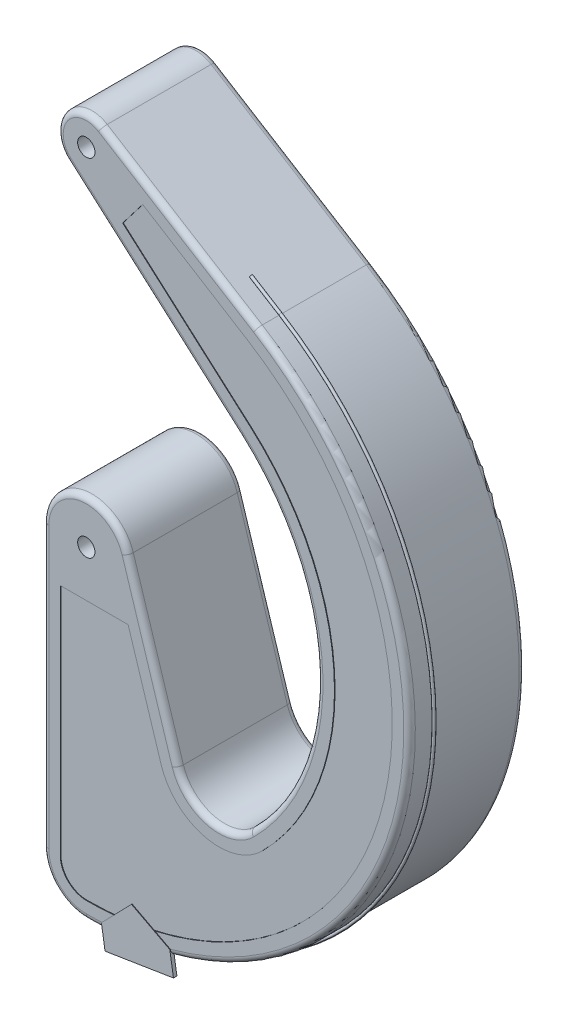
SolidWorks part; units mm, degrees
material "ABS"
ref_plane "Plan de face" through (0, 0, 0) normal (0, 0, 1) x (1, 0, 0)
ref_plane "Plan de dessus" through (0, 0, 0) normal (0, 1, 0) x (1, 0, 0)
ref_plane "Plan de droite" through (0, 0, 0) normal (1, 0, 0) x (0, 0, -1)
sketch "Esquisse1" plane through (0, 0, 0) normal (0, 0, 1) x (1, 0, 0)
  line L0 (0, 0) -> (0, -47.5) construction
  line L1 (0, 0) -> (22.981, -22.981) construction
  line L2 (-7.5, 0) -> (-7.5, -48.5)
  line L3 (7.1523, 2.257) -> (15.8286, -25.238)
  line L4 (-3.3072, 56.25) -> (26.4575, 30)
  line L6 (2.6339, 64.25) -> (29.4998, 47.6)
  circle A0 centre (0, 60) radius 1.5
  arc A2 (7.1523, 2.257) -> (-7.5, 0) centre (0, 0) ccw
  arc A4 (15.8286, -25.238) -> (28.2843, -28.2843) centre (22.981, -22.981) ccw
  arc A5 (2.6339, 64.25) -> (-3.3072, 56.25) centre (0, 60) ccw
  arc A6 (28.2843, -28.2843) -> (26.4575, 30) centre (0, 0) ccw
  circle A7 centre (0, 0) radius 1.5
  arc A8 (0, -56) -> (29.4998, 47.6) centre (0, 0) ccw
  arc A10 (0, -56) -> (-7.5, -48.5) centre (0, -48.5) cw
  dimension "D2" = 15
  dimension "D3" = 56
  dimension "D4" = 15
  dimension "D5" = 10
  dimension "D7" = 3
  dimension "D8" = 3
  dimension "D10" = 7.5
  dimension "D11" = 40
  dimension "D6" = 45
  dimension "D9" = 32.5
extrude "Boss.-Extru.1" add sketch "Esquisse1" along normal mid plane 20
fillet "Congé1" radius 1 20 edges at (-7.5, -24.25, -10) (-1.1418, 7.4126, -10) (11.4905, -11.4905, -10) (21.1992, -30.2662, -10) (39.9804, 1.2531, -10) (-4.0141, 62.9811, -10) (11.5752, 43.125, -10) (-7.5, -24.25, 10) (-1.1418, 7.4126, 10) (11.4905, -11.4905, 10) (21.1992, -30.2662, 10) (39.9804, 1.2531, 10) (11.5752, 43.125, 10) (-4.0141, 62.9811, 10) (16.0669, 55.925, -10) (53.8591, -15.3362, -10) (-5.3033, -53.8033, -10) (16.0669, 55.925, 10) (53.8591, -15.3362, 10) (-5.3033, -53.8033, 10)
sketch "Esquisse2" plane through (0, 0, 10) normal (0, 0, 1) x (1, 0, 0)
  line L0 (14.5662, -53.0361) -> (15.1984, -56.9858)
  line L1 (15.1984, -56.9858) -> (3.3493, -58.8826)
  line L2 (3.3493, -58.8826) -> (2.717, -54.9328)
  line L3 (2.717, -54.9328) -> (7.9333, -49.56)
  line L4 (7.9333, -49.56) -> (14.5662, -53.0361)
  line L6 (0, 0) -> (9.2738, -57.9342) construction
  arc A1 (0, -55) -> (28.973, 46.75) centre (0, 0) ccw construction
  dimension "D2" = 6
  dimension "D3" = 4
extrude "Boss.-Extru.2" add sketch "Esquisse2" against normal blind 0.5 and the other way blind 0.1
sketch "Esquisse4" plane through (0, 0, -10) normal (0, 0, -1) x (-1, 0, 0)
  line L0 (-7.2432, -8) -> (4.5, -8)
  line L5 (-1.0536, 61.7) -> (-27.9195, 45.05)
  line L6 (-9.7625, 56.3027) -> (-27.9195, 45.05)
  line L8 (-6.2999, 51.7773) -> (-9.7625, 56.3027)
  line L9 (0, 60) -> (-7.9419, 53.9233) construction
  line L12 (4.5, -48.5) -> (4.5, 0)
  line L13 (-4.2914, 1.3542) -> (-12.9677, -26.1408)
  line L14 (-28.4418, 32.25) -> (1.3229, 58.5)
  line L16 (4.5, -48.5) -> (4.5, -8)
  line L17 (-7.2432, -8) -> (-12.9677, -26.1408)
  line L18 (-28.4418, 32.25) -> (-6.2999, 51.7773)
  arc A6 (-27.9195, 45.05) -> (0, -53) centre (0, 0) ccw
  arc A7 (-27.9195, 45.05) -> (0, -53) centre (0, 0) ccw
  arc A8 (0, -53) -> (4.5, -48.5) centre (0, -48.5) ccw
  arc A9 (0, -53) -> (4.5, -48.5) centre (0, -48.5) ccw
  arc A20 (4.5, 0) -> (-4.2914, 1.3542) centre (0, 0) ccw
  arc A21 (-30.4056, -30.4056) -> (-12.9677, -26.1408) centre (-22.981, -22.981) ccw
  arc A22 (-28.4418, 32.25) -> (-30.4056, -30.4056) centre (0, 0) ccw
  arc A23 (1.3229, 58.5) -> (-1.0536, 61.7) centre (0, 60) ccw
  arc A27 (-30.4056, -30.4056) -> (-12.9677, -26.1408) centre (-22.981, -22.981) ccw
  arc A28 (-28.4418, 32.25) -> (-30.4056, -30.4056) centre (0, 0) ccw
  dimension "D2" = 10
  dimension "D1" = 2
extrude "Enlèv. mat.-Extru.2" cut sketch "Esquisse4" against normal blind 0.1
mirror "Symétrie1" about plane through (0, 0, 0) normal (0, 0, 1) of "Enlèv. mat.-Extru.2"
sketch "Esquisse5" plane through (-7.5, 0, 0) normal (-1, 0, 0) x (0, 0, 1)
  line L0 (9, 0) -> (-9, 0) construction
  line L1 (-6, -43.5) -> (6, -43.5)
  line L2 (-6, -43.5) -> (-6, -5.5)
  line L3 (-6, -5.5) -> (6, -5.5)
  line L4 (6, -43.5) -> (6, -5.5)
  point P4 (0, 0)
  dimension "D1" = 6
  dimension "D2" = 12
  dimension "D3" = 5.5
  dimension "D4" = 38
extrude "Enlèv. mat.-Extru.3" cut sketch "Esquisse5" against normal blind 10
sketch "Esquisse6" plane through (0, 0, -6) normal (0, 0, 1) x (1, 0, 0)
  line L0 (2.5, -43.5) -> (-7.5, -43.5) construction
  line L1 (-7.5, -5.5) -> (-7.5, -43.5) construction
  circle A0 centre (-3.5, -39.5) radius 1
  dimension "D1" = 2
  dimension "D2" = 4
  dimension "D3" = 4
extrude "Boss.-Extru.3" add sketch "Esquisse6" along normal up to surface (12 mm away) up to face at (-2.5, -24.5, 6)
ref_plane "Plan1" through (-4, 0, 0) normal (-1, 0, 0) x (0, 0, 1)
sketch "Esquisse7" plane through (-4, 0, 0) normal (-1, 0, 0) x (0, 0, 1)
  line L0 (7.4765, -15.1329) -> (1, -18.8721)
  line L1 (-1, -18.8721) -> (-7.4765, -15.1329)
  line L2 (0, -34.925) -> (0, 34.925) construction
  line L3 (9, -22.981) -> (-9, -22.981) construction
  arc A1 (1, -18.8721) -> (-1, -18.8721) centre (0, -17.14) cw
  point P11 (-5.9762, -21.4854)
  dimension "D3" = 120
  dimension "D1" = 2
  dimension "D4" = 30
sketch "Esquisse9" plane through (0, 0, 0) normal (0, 0, 1) x (1, 0, 0)
  circle A0 centre (-4, -19.14) radius 0.25
  dimension "D1" = 0.5
sweep "Balayage1" add profiles "Esquisse9" path "Esquisse7"
mirror "Symétrie2" of "Balayage1"
sketch "Esquisse10" plane through (0, 0, 6) normal (0, 0, -1) x (-1, 0, 0)
  line L7 (-2.5, -43.5) -> (7.5, -43.5) construction
  line L8 (7.75, -48.5) -> (7.75, 0)
  line L10 (-2.7656, 64.4625) -> (-29.6315, 47.8125)
  line L11 (7.75, -48.5) -> (7.75, -43.5)
  line L12 (-24.5315, 50.9732) -> (-29.6315, 47.8125)
  arc A4 (0, -56.25) -> (7.75, -48.5) centre (0, -48.5) ccw
  arc A5 (-29.6315, 47.8125) -> (0, -56.25) centre (0, 0) ccw
  arc A6 (0, -56.25) -> (7.75, -48.5) centre (0, -48.5) ccw
  arc A7 (-29.6315, 47.8125) -> (0, -56.25) centre (0, 0) ccw
  dimension "D2" = 6
  dimension "D1" = 0.25
sketch "Esquisse11" plane through (0, -43.5, 0) normal (0, 1, 0) x (1, 0, 0)
  circle A0 centre (-7.75, -6) radius 0.25
  dimension "D1" = 0.5
  dimension "D2" = 0.5
ref_plane "Plan2" through (27.9195, 45.05, 0) normal (-0.5268, -0.85, 0) x (0.85, -0.5268, 0)
sweep "Balayage3" add profiles "Esquisse11" path "Esquisse10"
